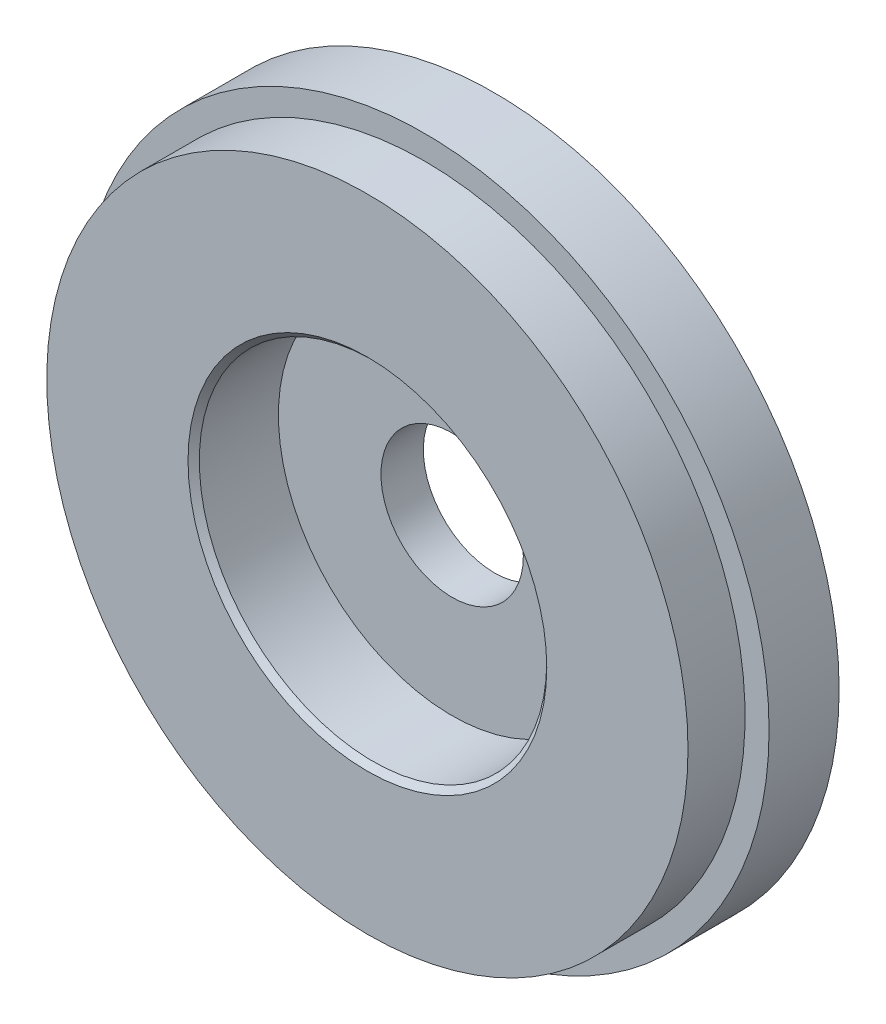
SolidWorks part; units mm, degrees
material "尼龙 6/10"
ref_plane "前视基准面" through (0, 0, 0) normal (0, 0, 1) x (1, 0, 0)
ref_plane "上视基准面" through (0, 0, 0) normal (0, 1, 0) x (1, 0, 0)
ref_plane "右视基准面" through (0, 0, 0) normal (1, 0, 0) x (0, 0, -1)
sketch "草图1" plane through (0, 0, 0) normal (0, 0, 1) x (1, 0, 0)
  circle A0 centre (-22.804, 9.3503) radius 12.2
extrude "凸台-拉伸1" add sketch "草图1" along normal blind 2.48 from surface at 2.5
sketch "草图2" plane through (0, 0, 0) normal (0, 0, 1) x (1, 0, 0)
  circle A0 centre (-22.804, 9.3503) radius 11.35
extrude "凸台-拉伸2" add sketch "草图2" along normal up to surface (2.02 mm away) from surface at 4.98 starting at face at (-22.804, -2.8497, 4.98)
sketch "草图3" plane through (0, 0, 0) normal (0, 0, 1) x (1, 0, 0)
  circle A0 centre (-22.804, 9.3503) radius 6.15
extrude "切除-拉伸1" cut sketch "草图3" against normal blind 3 from surface at 7 starting at face at (-11.454, 9.3503, 7)
chamfer "倒角1" distance 0.2 angle 45 1 edges at (-16.654, 9.3503, 7)
sketch "草图4" plane through (0, 0, 0) normal (0, 0, 1) x (1, 0, 0)
  circle A0 centre (-22.804, 9.3503) radius 2.52
extrude "切除-拉伸2" cut sketch "草图4" against normal up to next from surface
